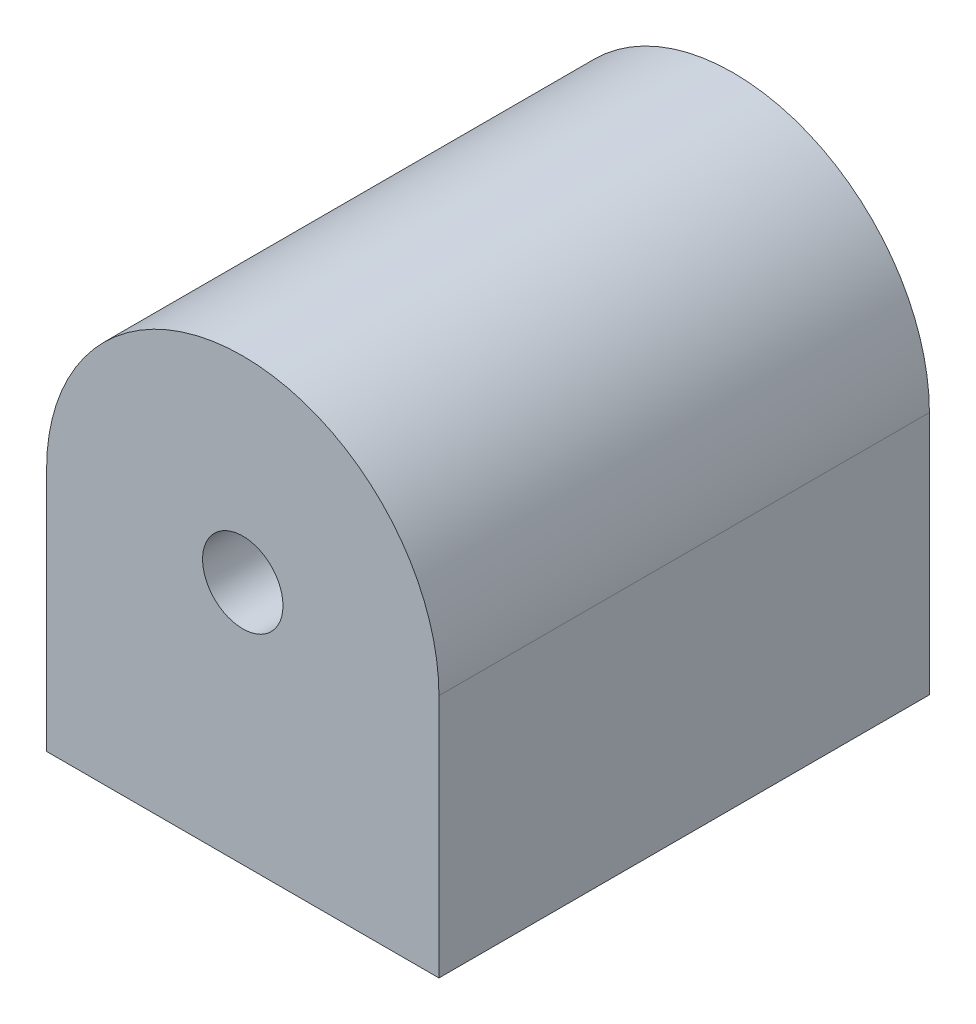
SolidWorks part; units mm, degrees
ref_plane "Alzado" through (0, 0, 0) normal (0, 0, 1) x (1, 0, 0)
ref_plane "Planta" through (0, 0, 0) normal (0, 1, 0) x (1, 0, 0)
ref_plane "Vista lateral" through (0, 0, 0) normal (1, 0, 0) x (0, 0, -1)
sketch "Croquis1" plane through (0, 0, 0) normal (0, 0, 1) x (1, 0, 0)
  line L2 (-40, 0) -> (-40, -49.8472)
  line L3 (-40, -49.8472) -> (40, -49.8472)
  line L4 (40, 0) -> (40, -49.8472)
  arc A0 (40, 0) -> (-40, 0) centre (0, 0) ccw
  circle A1 centre (0, 0) radius 8.1955
  dimension "D1" = 80
extrude "Saliente-Extruir1" add sketch "Croquis1" along normal mid plane 100
